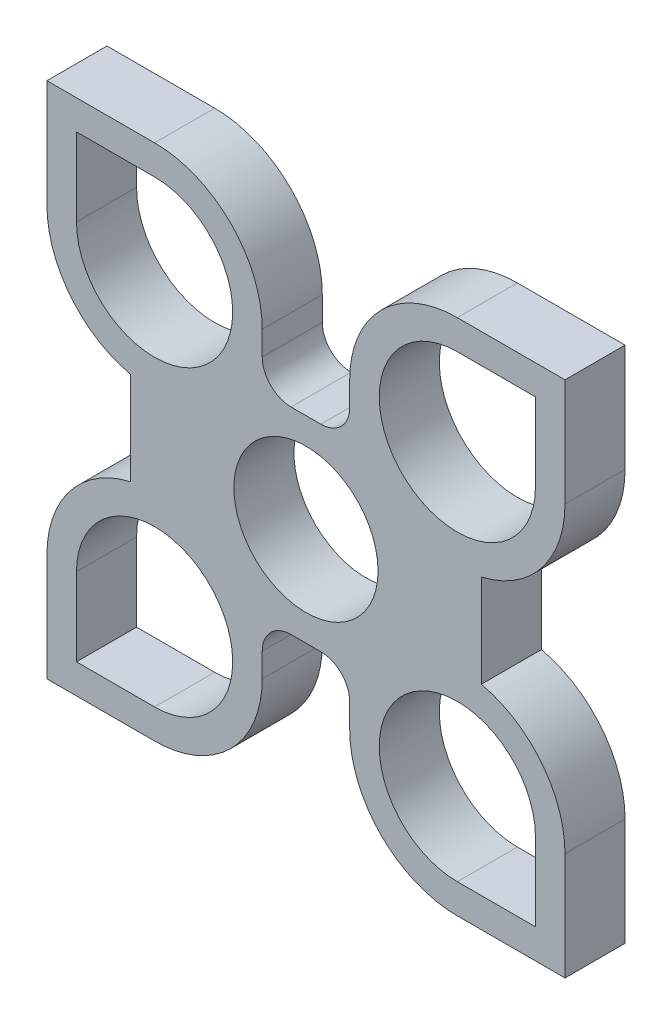
SolidWorks part; units mm, degrees
ref_plane "Front Plane" through (0, 0, 0) normal (0, 0, 1) x (1, 0, 0)
ref_plane "Top Plane" through (0, 0, 0) normal (0, 1, 0) x (1, 0, 0)
ref_plane "Right Plane" through (0, 0, 0) normal (1, 0, 0) x (0, 0, -1)
sketch "Sketch2" plane through (0, 0, 0) normal (0, 0, 1) x (1, 0, 0)
  line L0 (0, 87.7664) -> (0, -87.7664) construction
  line L1 (-85.9982, 0) -> (85.9982, 0) construction
  line L2 (63, 107.8) -> (107.8, 107.8)
  line L3 (107.8, 107.8) -> (107.8, 63)
  line L4 (63, 95.5) -> (95.5, 95.5)
  line L5 (95.5, 95.5) -> (95.5, 63)
  line L6 (73, 19.3303) -> (73, -19.3303)
  line L7 (-6.2, 41) -> (6.2, 41)
  line L8 (18.2, 53) -> (18.2, 63)
  line L9 (95.5, -95.5) -> (95.5, -63)
  line L10 (63, -95.5) -> (95.5, -95.5)
  line L11 (107.8, -107.8) -> (107.8, -63)
  line L12 (63, -107.8) -> (107.8, -107.8)
  line L13 (18.2, -53) -> (18.2, -63)
  line L14 (-6.2, -41) -> (6.2, -41)
  line L15 (-18.2, -53) -> (-18.2, -63)
  line L16 (-63, -107.8) -> (-107.8, -107.8)
  line L17 (-107.8, -107.8) -> (-107.8, -63)
  line L18 (-63, -95.5) -> (-95.5, -95.5)
  line L19 (-95.5, -95.5) -> (-95.5, -63)
  line L20 (-18.2, 53) -> (-18.2, 63)
  line L21 (-73, 19.3303) -> (-73, -19.3303)
  line L22 (-95.5, 95.5) -> (-95.5, 63)
  line L23 (-63, 95.5) -> (-95.5, 95.5)
  line L24 (-107.8, 107.8) -> (-107.8, 63)
  line L25 (-63, 107.8) -> (-107.8, 107.8)
  circle A0 centre (0, 0) radius 30
  arc A1 (63, 95.5) -> (95.5, 63) centre (63, 63) ccw
  arc A2 (63, 107.8) -> (18.2, 63) centre (63, 63) ccw
  arc A5 (73, 19.3303) -> (107.8, 63) centre (63, 63) ccw
  arc A6 (18.2, 53) -> (6.2, 41) centre (6.2, 53) cw
  arc A7 (63, -95.5) -> (95.5, -63) centre (63, -63) cw
  arc A8 (73, -19.3303) -> (107.8, -63) centre (63, -63) cw
  arc A9 (63, -107.8) -> (18.2, -63) centre (63, -63) cw
  arc A10 (18.2, -53) -> (6.2, -41) centre (6.2, -53) ccw
  arc A11 (-18.2, -53) -> (-6.2, -41) centre (-6.2, -53) cw
  arc A12 (-63, -107.8) -> (-18.2, -63) centre (-63, -63) ccw
  arc A13 (-73, -19.3303) -> (-107.8, -63) centre (-63, -63) ccw
  arc A14 (-63, -95.5) -> (-95.5, -63) centre (-63, -63) ccw
  arc A15 (-18.2, 53) -> (-6.2, 41) centre (-6.2, 53) ccw
  arc A16 (-73, 19.3303) -> (-107.8, 63) centre (-63, 63) cw
  arc A17 (-63, 107.8) -> (-18.2, 63) centre (-63, 63) cw
  arc A18 (-63, 95.5) -> (-95.5, 63) centre (-63, 63) cw
  point P4 (0, 0)
  point P7 (0, 0)
  point P23 (-73, 0)
  point P29 (73, 0)
  point P37 (0, -41)
  point P59 (0, 41)
  dimension "D1" = 60
  dimension "D2" = 65
  dimension "D3" = 89.6
  dimension "D7" = 12
  dimension "D8" = 11.3614
  dimension "D4" = 63
  dimension "D5" = 63
  dimension "D6" = 73
extrude "Boss-Extrude1" add sketch "Sketch2" along normal blind 25
